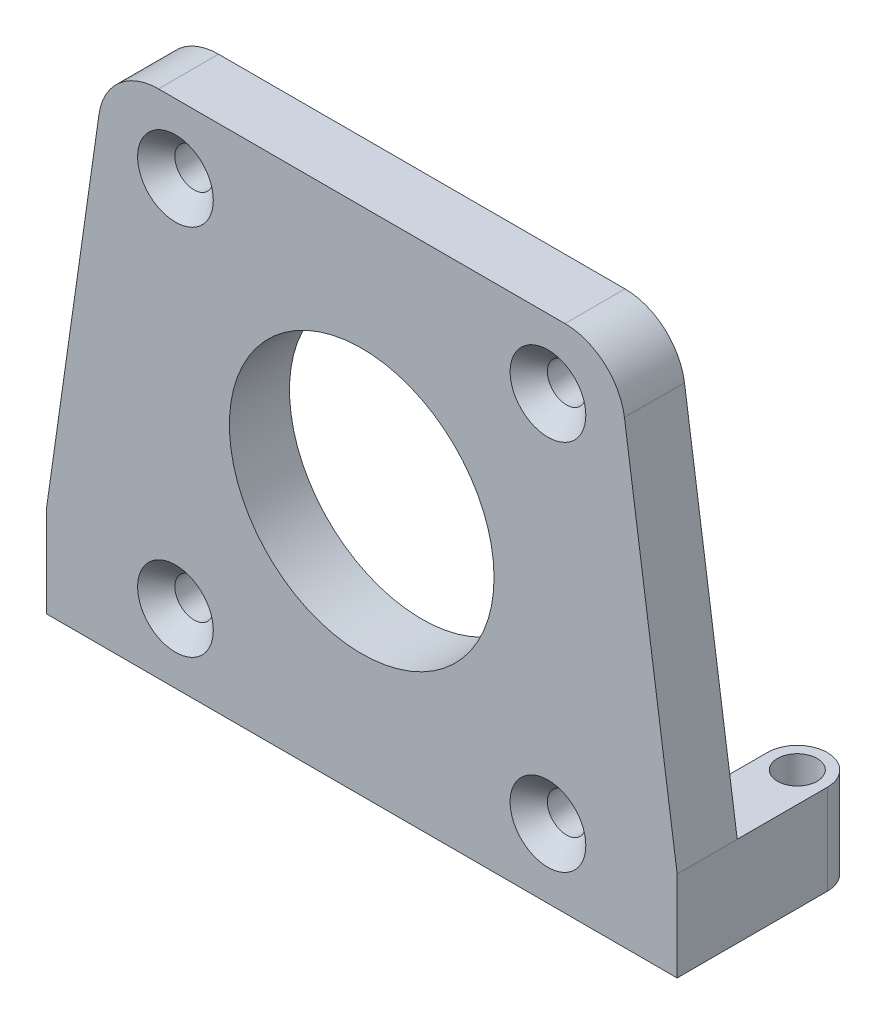
SolidWorks part; units mm, degrees
ref_plane "Ebene vorne" through (0, 0, 0) normal (0, 0, 1) x (1, 0, 0)
ref_plane "Ebene oben" through (0, 0, 0) normal (0, 1, 0) x (1, 0, 0)
ref_plane "Ebene rechts" through (0, 0, 0) normal (1, 0, 0) x (0, 0, -1)
sketch "Skizze1" plane through (0, 0, 0) normal (0, 0, 1) x (1, 0, 0)
  line L0 (52.5, 7.5) -> (48.1133, 38.2071)
  line L1 (0, 0) -> (52.5, 0)
  line L2 (0, 0) -> (0, 7.5)
  line L3 (9.3365, 42.5) -> (43.1635, 42.5)
  line L4 (52.5, 0) -> (52.5, 7.5)
  line L5 (0, 7.5) -> (4.3867, 38.2071)
  line L6 (26.25, 21.25) -> (1.9643, 21.25) construction
  line L7 (26.25, 21.25) -> (50.5357, 21.25) construction
  circle A0 centre (26.25, 21.25) radius 11.0125
  arc A1 (4.3867, 38.2071) -> (9.3365, 42.5) centre (9.3365, 37.5) cw
  arc A2 (48.1133, 38.2071) -> (43.1635, 42.5) centre (43.1635, 37.5) ccw
  point P9 (5, 42.5)
  point P11 (0, 42.5)
  point P15 (47.5, 42.5)
  dimension "D2" = 22.025
  dimension "D6" = 7.5
  dimension "D9" = 5
  dimension "D1" = 52.5
  dimension "D3" = 42.5
  dimension "D5" = 21.25
  dimension "D7" = 5
  dimension "D8" = 5
extrude "Aufsatz-Linear austragen1" add sketch "Skizze1" along normal blind 5
sketch "Skizze4" plane through (0, 0, 0) normal (0, -1, 0) x (1, 0, 0)
  line L1 (52.5, 0) -> (47.5, 0)
  line L2 (52.5, 0) -> (52.5, -7.5)
  line L4 (47.5, 0) -> (47.5, -7.5)
  line L7 (0, 0) -> (5, 0)
  line L8 (0, 0) -> (0, -7.5)
  line L10 (5, 0) -> (5, -7.5)
  arc A0 (47.5, -7.5) -> (52.5, -7.5) centre (50, -7.5) ccw
  arc A1 (0, -7.5) -> (5, -7.5) centre (2.5, -7.5) ccw
  dimension "D1" = 2.5
  dimension "D2" = 7.5
extrude "Aufsatz-Linear austragen2" add sketch "Skizze4" against normal blind 7.5
hole_wizard "Formsenkung für M3 Senkschraube mit Schlitz/Kreuzschlitz1" positions "Skizze11" profile "Skizze10" countersink size "M3" standard "DIN" end condition through all
sketch "Skizze11" plane through (0, 0, 5) normal (0, 0, 1) x (1, 0, 0)
  line L1 (10.75, 36.75) -> (41.75, 36.75) construction
  line L2 (10.75, 36.75) -> (10.75, 5.75) construction
  line L3 (10.75, 5.75) -> (41.75, 5.75) construction
  line L4 (41.75, 36.75) -> (41.75, 5.75) construction
  circle A0 centre (26.25, 21.25) radius 21.9203 construction
  point P5 (10.75, 36.75)
  point P6 (41.75, 5.75)
  point P9 (10.75, 5.75)
  point P10 (41.75, 36.75)
  dimension "D1" = 31
sketch "Skizze10" plane through (10.75, 36.75, 5) normal (1, 0, 0) x (0, -1, 0)
  line L0 (0, 0) -> (0, 15)
  line L1 (0, 15) -> (1.6, 15)
  line L2 (1.6, 15) -> (1.6, 1.55)
  line L3 (1.6, 1.55) -> (3.15, 0)
  line L5 (3.15, 0) -> (0, 0)
  line L6 (-1.6, 1.55) -> (-3.15, 0) construction
  line L11 (0, -6.35) -> (0, 107.95) construction
  dimension "Bohrerdurchmesser" = 3.2
  dimension "Bohrungstiefe" = 15
  dimension "Senkdurchmesser (Oben)" = 6.3
  dimension "Senkwinkel (Oben)" = 90
hole_wizard "M4 Gewindebohrung2" positions "Skizze13" profile "Skizze14" tap size "M4" standard "DIN"
sketch "Skizze13" plane through (0, 0, 0) normal (0, -1, 0) x (-1, 0, 0)
  line L0 (0, -5) -> (-52.5, -5) construction
  point P2 (-2.5, 7.5)
  point P7 (-50, 7.5)
  point P11 (-50, -2.5)
  point P13 (-2.5, -2.5)
  dimension "D1" = 2.5
cosmetic thread "Bohrungsgewinde3" parameters "D1"=7.5, "D2"=4
cosmetic thread "Bohrungsgewinde4" parameters "D1"=7.5, "D2"=4
sketch "Skizze14" plane through (2.5, 0, -7.5) normal (1, 0, 0) x (0, 0, -1)
  line L0 (0, 0) -> (0, 13.9914)
  line L1 (0, 13.9914) -> (1.65, 13)
  line L2 (1.65, 13) -> (1.65, 0)
  line L5 (1.65, 0) -> (0, 0)
  line L10 (0, 13.9914) -> (-1.65, 13) construction
  line L11 (0, -6.35) -> (0, 107.95) construction
  dimension "Bohrerdurchmesser" = 3.3
  dimension "Bohrungstiefe" = 13
  dimension "Spitzenwinkel" = 118
cosmetic thread "Bohrungsgewinde5" parameters "D1"=10, "D2"=4
cosmetic thread "Bohrungsgewinde6" parameters "D1"=10, "D2"=4
